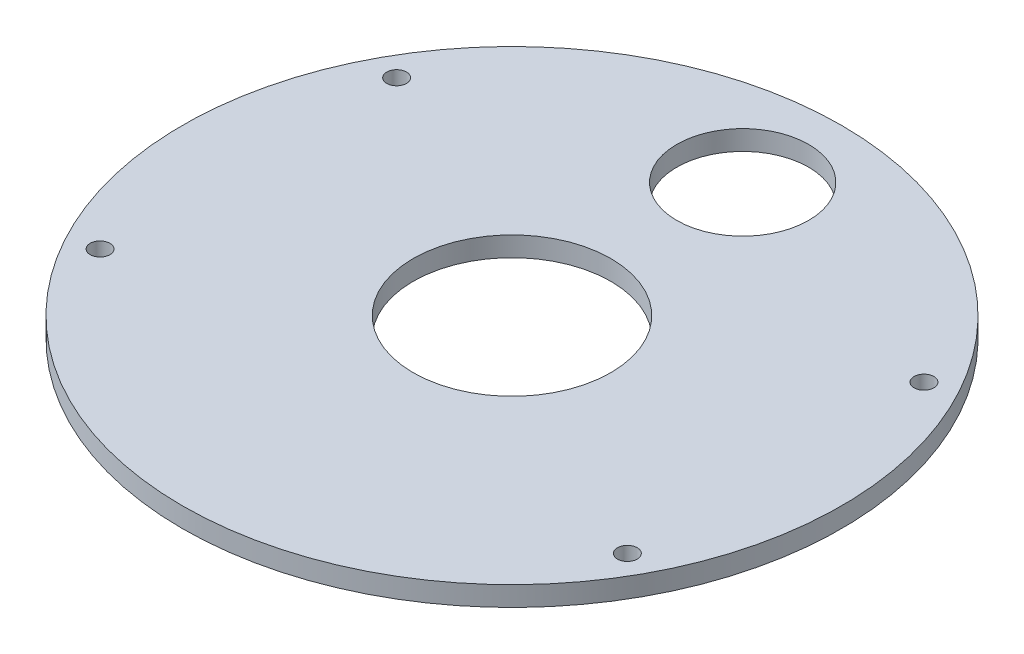
SolidWorks part; units mm, degrees
material "Cast Alloy Steel"
ref_plane "Front Plane" through (0, 0, 0) normal (0, 0, 1) x (1, 0, 0)
ref_plane "Top Plane" through (0, 0, 0) normal (0, 1, 0) x (1, 0, 0)
ref_plane "Right Plane" through (0, 0, 0) normal (1, 0, 0) x (0, 0, -1)
sketch "Sketch1" plane through (0, 0, 0) normal (0, 1, 0) x (1, 0, 0)
  line L1 (40, -22.5) -> (-40, -22.5) construction
  line L2 (40, -22.5) -> (40, 22.5) construction
  line L3 (40, 22.5) -> (-40, 22.5) construction
  line L4 (-40, -22.5) -> (-40, 22.5) construction
  line L5 (40, -22.5) -> (-40, 22.5) construction
  line L6 (40, 22.5) -> (-40, -22.5) construction
  circle A0 centre (0, 0) radius 50
  circle A1 centre (-40, 22.5) radius 1.5
  circle A2 centre (40, 22.5) radius 1.5
  circle A3 centre (40, -22.5) radius 1.5
  circle A4 centre (-40, -22.5) radius 1.5
  dimension "D1" = 100
  dimension "D4" = 3
  dimension "D2" = 80
  dimension "D3" = 45
extrude "Boss-Extrude1" add sketch "Sketch1" along normal blind 3
sketch "Sketch2" plane through (0, 3, 0) normal (0, 1, 0) x (1, 0, 0)
  circle A0 centre (0, 0) radius 15
  dimension "D1" = 30
extrude "Cut-Extrude1" cut sketch "Sketch2" against normal blind 10
sketch "Sketch3" plane through (0, 0, 0) normal (0, -1, 0) x (1, 0, 0)
  line L0 (0, 0) -> (0, -35) construction
  circle A0 centre (0, -35) radius 10
  dimension "D2" = 20
  dimension "D1" = 35
extrude "Cut-Extrude2" cut sketch "Sketch3" against normal blind 10
